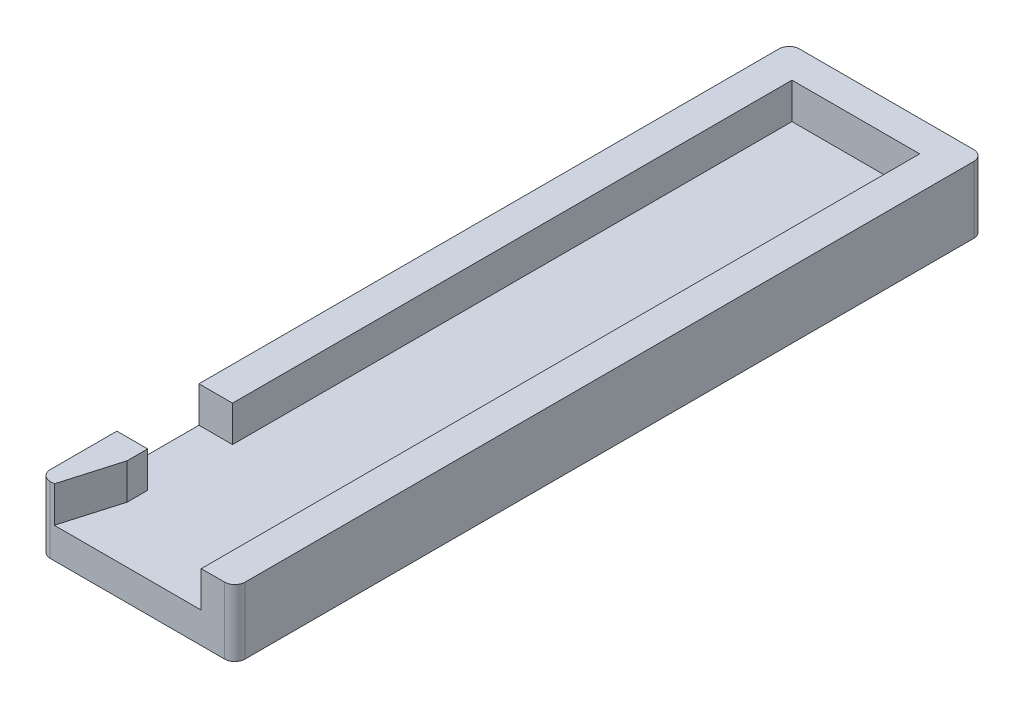
SolidWorks part; units mm, degrees
ref_plane "正面" through (0, 0, 0) normal (0, 0, 1) x (1, 0, 0)
ref_plane "平面" through (0, 0, 0) normal (0, 1, 0) x (1, 0, 0)
ref_plane "右側面" through (0, 0, 0) normal (1, 0, 0) x (0, 0, -1)
sketch "ｽｹｯﾁ1" plane through (0, 0, 0) normal (0, 1, 0) x (1, 0, 0)
  line L0 (0, 0) -> (7, 0)
  line L2 (7, 0) -> (12, 0)
  line L4 (12, 0) -> (19, 0)
  line L5 (19, 0) -> (19, 73.05)
  line L6 (19, 73.05) -> (0, 73.05)
  line L7 (0, 73.05) -> (0, 0)
  dimension "D1" = 73.05
  dimension "D2" = 19
extrude "ﾎﾞｽ - 押し出し1" add sketch "ｽｹｯﾁ1" along normal blind 3
sketch "ｽｹｯﾁ2" plane through (0, 3, 0) normal (0, 1, 0) x (1, 0, 0)
  line L0 (1.4, 0) -> (3, 5.5)
  line L1 (0, 0) -> (19, 0) construction
  line L2 (3, 5.5) -> (3, 7.5)
  line L3 (3, 7.5) -> (0, 7.5)
  line L4 (0, 73.05) -> (0, 0) construction
  line L5 (0, 7.5) -> (0, 0)
  line L6 (0, 0) -> (1.4, 0)
  line L7 (0, 15.5) -> (3.275, 15.5)
  line L8 (3.275, 15.5) -> (3.275, 70.05)
  line L9 (3.275, 70.05) -> (15.725, 70.05)
  line L10 (15.725, 70.05) -> (15.725, 0)
  line L11 (0, 0) -> (19, 0) construction
  line L12 (15.725, 0) -> (19, 0)
  line L13 (19, 0) -> (19, 73.05)
  line L14 (19, 73.05) -> (0, 73.05)
  line L15 (0, 73.05) -> (0, 15.5)
  line L16 (9.5, 70.05) -> (9.5, 0) construction
  line L17 (0, 0) -> (19, 0) construction
  dimension "D1" = 12.45
  dimension "D2" = 3
  dimension "D3" = 1.6
  dimension "D4" = 7.5
  dimension "D5" = 2
  dimension "D6" = 8
  dimension "D7" = 3
extrude "ﾎﾞｽ - 押し出し2" add sketch "ｽｹｯﾁ2" along normal blind 3.5
fillet "ﾌｨﾚｯﾄ3" radius 1 4 edges at (0, 3.25, -73.05) (19, 3.25, -73.05) (19, 3.25, 0) (0, 3.25, 0)
sketch "ｽｹｯﾁ5" plane through (0, 0, 0) normal (0, -1, 0) x (1, 0, 0)
  line L4 (18, 0) -> (1, 0)
  line L6 (18, 0) -> (1, 0)
  line L16 (0, -1) -> (0, -72.05)
  line L17 (1, -73.05) -> (18, -73.05)
  line L18 (19, -72.05) -> (19, -1)
  line L24 (0, -1) -> (0, -72.05)
  line L25 (1, -73.05) -> (18, -73.05)
  line L26 (19, -72.05) -> (19, -1)
  arc A4 (19, -1) -> (18, 0) centre (18, -1) ccw
  arc A5 (19, -1) -> (18, 0) centre (18, -1) ccw
  arc A8 (0, -72.05) -> (1, -73.05) centre (1, -72.05) ccw
  arc A9 (18, -73.05) -> (19, -72.05) centre (18, -72.05) ccw
  arc A11 (1, 0) -> (0, -1) centre (1, -1) ccw
  arc A12 (0, -72.05) -> (1, -73.05) centre (1, -72.05) ccw
  arc A13 (18, -73.05) -> (19, -72.05) centre (18, -72.05) ccw
  arc A15 (1, 0) -> (0, -1) centre (1, -1) ccw
  dimension "D1" = 0
extrude "ｶｯﾄ - 押し出し2" [suppressed] cut sketch "ｽｹｯﾁ5" against normal blind 4.5
